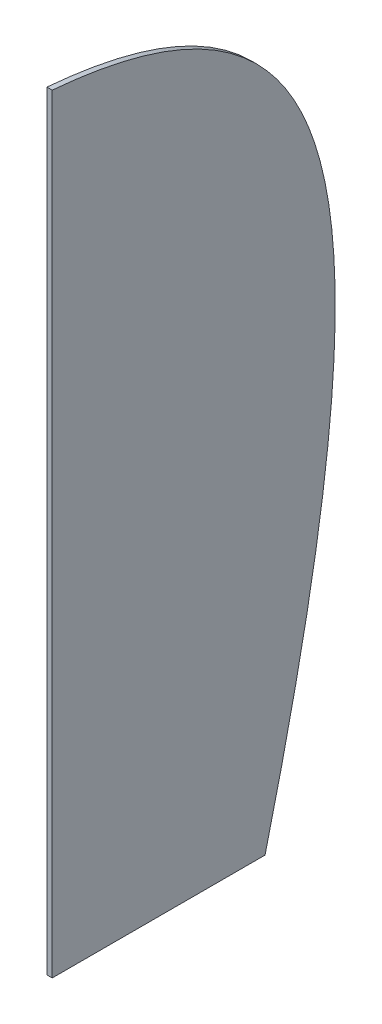
SolidWorks part; units mm, degrees
ref_plane "前视基准面" through (0, 0, 0) normal (0, 0, 1) x (1, 0, 0)
ref_plane "上视基准面" through (0, 0, 0) normal (0, 1, 0) x (1, 0, 0)
ref_plane "右视基准面" through (0, 0, 0) normal (1, 0, 0) x (0, 0, -1)
sketch "草图1" plane through (0, 0, 0) normal (0, 0, 1) x (1, 0, 0)
  line L0 (144.2985, 0) -> (0, 0) construction
  line L1 (0, 0) -> (0, -67.6179) construction
  line L2 (15, 6) -> (145, 6) construction
  line L3 (145, 6) -> (145, 0) construction
  line L4 (15, 6) -> (15, 0) construction
  line L5 (0, 0) -> (0, -71.7115) construction
  line L10 (0, 0) -> (145, -37) construction
  line L11 (145, -4) -> (18, -39.7537) construction
  line L12 (0, 0) -> (33.0829, -39.4266) construction
  line L13 (0, -40.144) -> (145, -37) construction
  line L14 (145, -37) -> (145, 0) construction
  line L17 (15, 0) -> (145, 0)
  line L21 (0, -40.144) -> (96.1056, -64.0701) construction
  line L22 (96.1056, -64.0701) -> (140.0538, -58.2825) construction
  line L23 (140.0538, -58.2825) -> (145, 0) construction
  line L24 (0, -40.144) -> (0, 0)
  line L25 (0, 0) -> (15, 0)
  spline S0 degree 3 poles (0, -40.144) (96.1056, -64.0701) (140.0538, -58.2825) (145, 0) knots 0 0 0 0 1 1 1 1
  dimension "D5" = 0
  dimension "D1" = 6
  dimension "D2" = 145
  dimension "D8" = 40
  dimension "D9" = 18
  dimension "D10" = 4
  dimension "D11" = 37
extrude "凸台-拉伸1" add sketch "草图1" along normal mid plane 1
fillet "圆角1" [suppressed] radius 5
move or copy body "实体-移动/复制1" bodies to move or copy 101 copy no rotation origin (0, 0, 0) rotation axis (0, 1, 0) rotation angle 180
move or copy body "实体-移动/复制2" bodies to move or copy 103 copy no rotation origin (0, 0, 0) rotation axis (0, 0, -1) rotation angle 90
move or copy body "实体-移动/复制3" bodies to move or copy 104 copy no rotation origin (0, 0, 0) rotation axis (0, -1, 0) rotation angle 90
